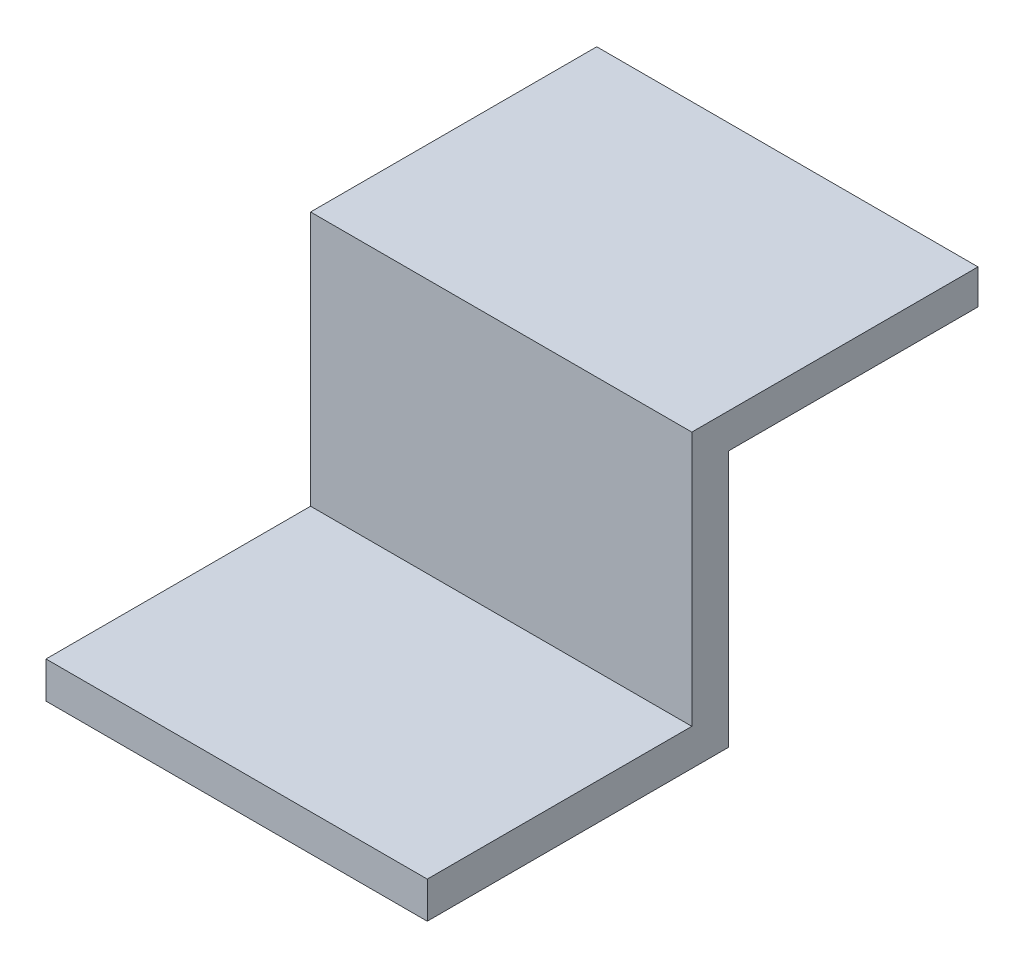
SolidWorks part; units mm, degrees
ref_plane "Front Plane" through (0, 0, 0) normal (0, 0, 1) x (1, 0, 0)
ref_plane "Top Plane" through (0, 0, 0) normal (0, 1, 0) x (1, 0, 0)
ref_plane "Right Plane" through (0, 0, 0) normal (1, 0, 0) x (0, 0, -1)
sketch "Sketch10" plane through (0, 0, 0) normal (1, 0, 0) x (0, 0, -1)
  line L0 (52.3533, 44.6272) -> (52.3533, 0)
  line L1 (52.3533, 0) -> (0, 0)
  line L2 (0, 0) -> (0, 6.35)
  line L3 (0, 6.35) -> (46.0033, 6.35)
  line L4 (46.0033, 6.35) -> (46.0033, 50.6588)
  line L5 (46.0033, 50.6588) -> (52.3533, 50.6588)
  line L7 (52.3533, 50.6588) -> (95.7628, 50.6588)
  line L9 (52.3533, 44.6272) -> (95.7628, 44.6272)
  line L10 (95.7628, 50.6588) -> (95.7628, 44.6272)
extrude "Extrude4" add sketch "Sketch10" against normal blind 66.294
ref_plane "Plane3" through (0, 3.2941, 3.1728) normal (0, -0.7202, -0.6937) x (1, 0, 0)
sketch "Sketch11" plane through (0, 3.2941, 3.1728) normal (0, -0.7202, -0.6937) x (1, 0, 0)
  line L0 (0, -68.2766) -> (0, -4.4051)
